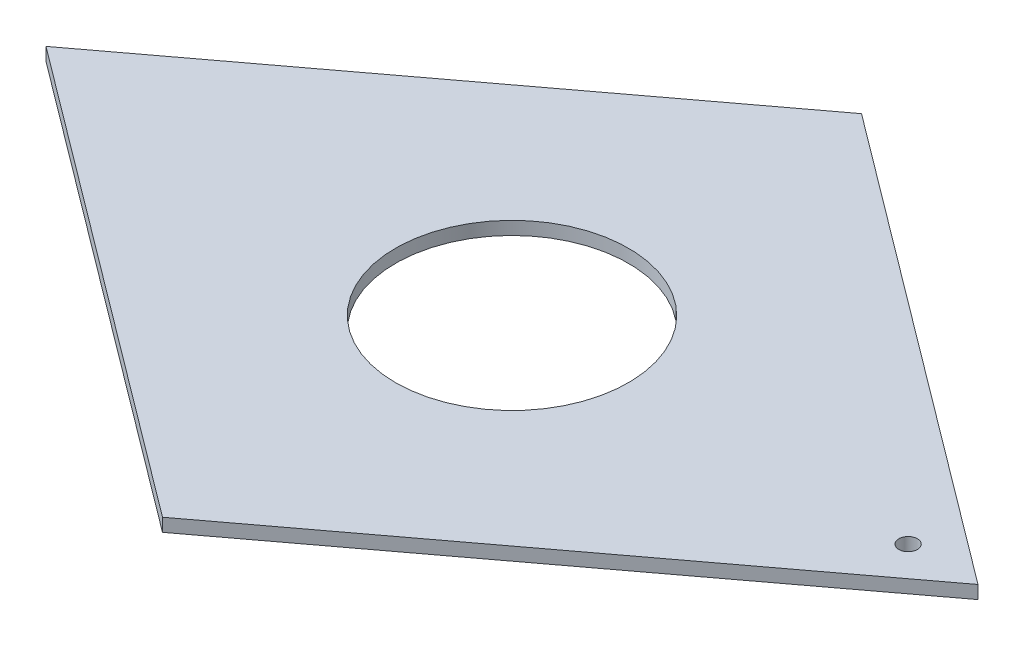
SolidWorks part; units mm, degrees
ref_plane "Front Plane" through (0, 0, 0) normal (0, 0, 1) x (1, 0, 0)
ref_plane "Top Plane" through (0, 0, 0) normal (0, 1, 0) x (1, 0, 0)
ref_plane "Right Plane" through (0, 0, 0) normal (1, 0, 0) x (0, 0, -1)
sketch "Sketch1" plane through (0, 0, 0) normal (0, 1, 0) x (1, 0, 0)
  line L20 (0, 150) -> (200, 0)
  line L21 (200, 0) -> (0, -150)
  line L22 (0, -150) -> (-200, 0)
  line L23 (-200, 0) -> (0, 150)
  circle A0 centre (0, 0) radius 50
  circle A1 centre (170, 0) radius 4
  dimension "D4" = 100
  dimension "D6" = 8
  dimension "D1" = 400
  dimension "D3" = 300
  dimension "D2" = 200
  dimension "D5" = 30
extrude "Boss-Extrude1" add sketch "Sketch1" along normal blind 5.63
equation "\"Side\"= 170.5"
equation "\"thick acrylic\"= 5.63"
equation "\"connect width\"= 15"
equation "\"thin acrylic\"= 2.95"
equation "\"width\"= 300"
equation "\"length\"= 400"
equation "\"D1@Boss-Extrude1\"=\"thick acrylic\""
equation "\"D1@Sketch1\"=\"length\""
equation "\"D3@Sketch1\"=\"width\""
equation "\"D2@Sketch1\"=\"length\"/2"
equation "\"lens hole\"= 100"
equation "\"D4@Sketch1\"=\"lens hole\""
